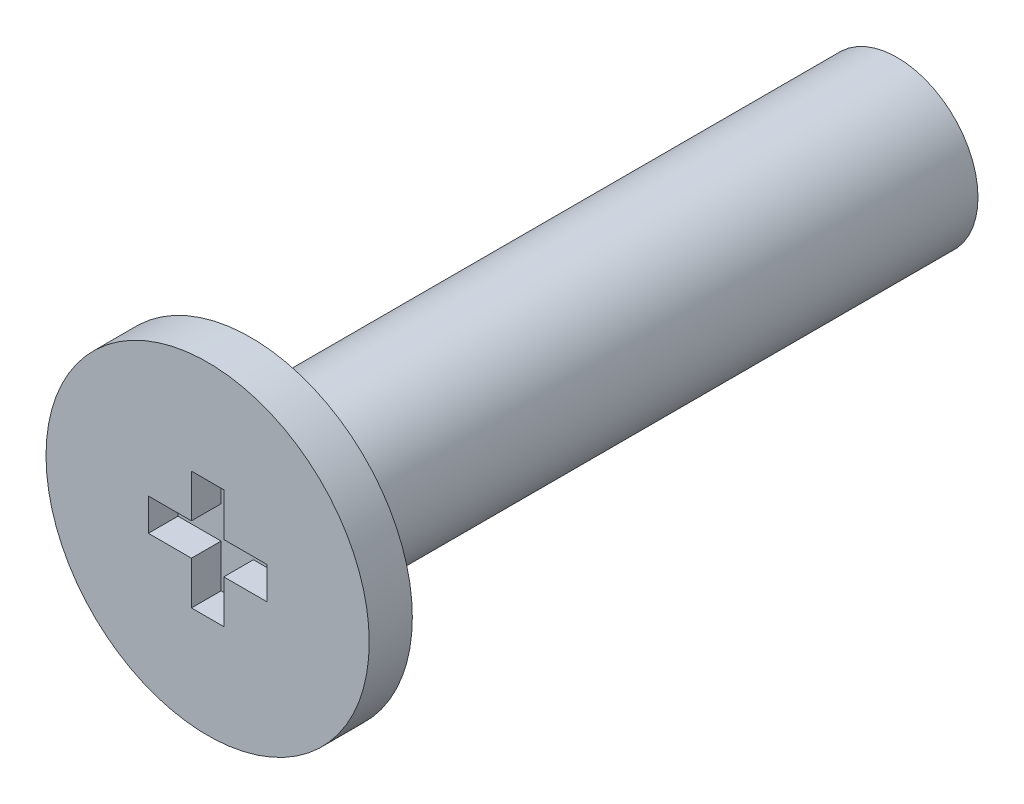
SolidWorks part; units mm, degrees
ref_plane "前视基准面" through (0, 0, 0) normal (0, 0, 1) x (1, 0, 0)
ref_plane "上视基准面" through (0, 0, 0) normal (0, 1, 0) x (1, 0, 0)
ref_plane "右视基准面" through (0, 0, 0) normal (1, 0, 0) x (0, 0, -1)
other "Configuration Table"
sketch "草图1" plane through (0, 0, 0) normal (0, 0, 1) x (1, 0, 0)
  circle A0 centre (0, 0) radius 1.5
extrude "标准杆径_头下长度" add sketch "草图1" against normal blind 12
sketch "草图2" plane through (0, 0, 0) normal (0, 0, 1) x (1, 0, 0)
  circle A0 centre (0, 0) radius 2.75
sketch "草图4" plane through (0, 0, 0) normal (0, 1, 0) x (1, 0, 0)
  line L0 (0, 0) -> (3.45, 0)
  line L1 (3.45, 0) -> (3.45, -0.3426)
  line L2 (0, -1.9) -> (0, 0)
  line L3 (0, 2) -> (0, -3.9) construction
  arc A0 (3.45, -0.3426) -> (0, -1.9) centre (0, 2.7) cw
sketch "草图5" plane through (0, 0, 0) normal (0, 0, 1) x (1, 0, 0)
  line L0 (-0.3, -1.45) -> (0.3, -1.45)
  line L1 (0.3, -1.45) -> (0.3, -0.3)
  line L2 (0.3, -0.3) -> (1.45, -0.3)
  line L3 (1.45, -0.3) -> (1.45, 0.3)
  line L4 (1.45, 0.3) -> (0.3, 0.3)
  line L5 (0.3, 0.3) -> (0.3, 1.45)
  line L6 (0.3, 1.45) -> (-0.3, 1.45)
  line L7 (-0.3, 1.45) -> (-0.3, 0.3)
  line L8 (-0.3, 0.3) -> (-1.45, 0.3)
  line L9 (-1.45, 0.3) -> (-1.45, -0.3)
  line L10 (-1.45, -0.3) -> (-0.3, -0.3)
  line L11 (-0.3, -0.3) -> (-0.3, -1.45)
sketch "草图6" plane through (0, 0, 0) normal (0, 1, 0) x (1, 0, 0)
  line L0 (0, 0) -> (3, 0)
  line L1 (3, 0) -> (3, -0.8)
  line L2 (3, -0.8) -> (0, -0.8)
  line L3 (0, -0.8) -> (0, 0)
  line L4 (0, 2) -> (0, -2.8) construction
revolve "已确认_十字槽超薄头" add sketch "草图6" angle 360 about L4
sketch "草图7" plane through (0, 0, 0) normal (0, 0, 1) x (1, 0, 0)
  line L0 (-0.3, -1.1) -> (0.3, -1.1)
  line L1 (0.3, -1.1) -> (0.3, -0.3)
  line L2 (0.3, -0.3) -> (1.1, -0.3)
  line L3 (1.1, -0.3) -> (1.1, 0.3)
  line L4 (1.1, 0.3) -> (0.3, 0.3)
  line L5 (0.3, 0.3) -> (0.3, 1.1)
  line L6 (0.3, 1.1) -> (-0.3, 1.1)
  line L7 (-0.3, 1.1) -> (-0.3, 0.3)
  line L8 (-0.3, 0.3) -> (-1.1, 0.3)
  line L9 (-1.1, 0.3) -> (-1.1, -0.3)
  line L10 (-1.1, -0.3) -> (-0.3, -0.3)
  line L11 (-0.3, -0.3) -> (-0.3, -1.1)
extrude "十字槽_PH1_简化" cut sketch "草图7" against normal blind 0.56 from offset 0.81
